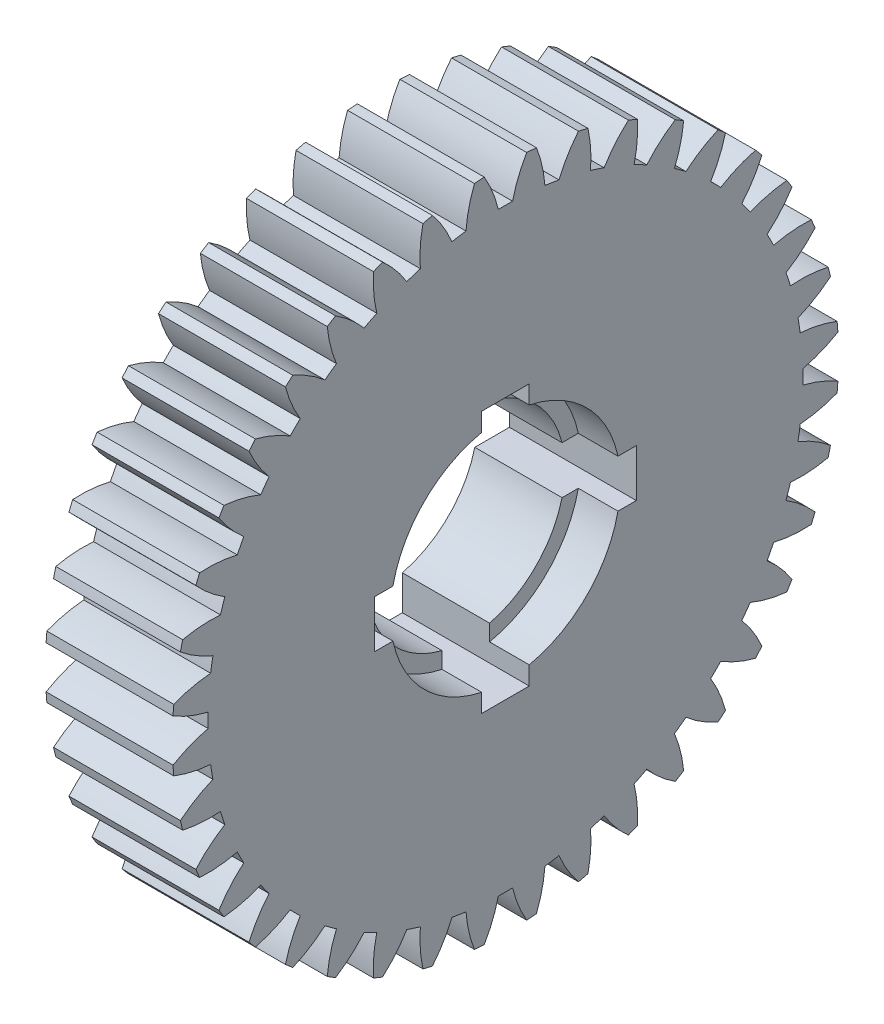
SolidWorks part; units mm, degrees
ref_plane "Plane1" through (0, 0, 0) normal (0, 0, 1) x (1, 0, 0)
ref_plane "Plane2" through (0, 0, 0) normal (0, 1, 0) x (1, 0, 0)
ref_plane "Plane3" through (0, 0, 0) normal (1, 0, 0) x (0, 0, -1)
sketch "HoldingSke" plane through (0, 0, 0) normal (0, 1, 0) x (1, 0, 0)
  line L0 (0, 0) -> (0.766, -0.6428)
  line L1 (-15, 0) -> (100, 0) construction
  line L2 (0, 0) -> (-2.1039, 2.3779)
  line L3 (0, 0) -> (-11.863, 4.5341)
  line L4 (0, 0) -> (6.6156, 5.5511)
  line L5 (0, 0) -> (-46.8476, -17.4728)
  line L6 (0, 0) -> (-6.6317, -4.4744)
  line L7 (-2.1039, 2.3779) -> (8.6586, 51.2059)
  line L8 (-76.2, 54.61) -> (-75.3, 54.61)
  line L9 (-71.009, 38.7566) -> (-53.1078, 45.2721)
  line L10 (-76.2, 71.12) -> (104.1128, 71.12)
  line L11 (0, 0) -> (-8, 0)
  line L12 (-76.2, 101.6) -> (-76.162, 101.6)
  line L13 (24.9733, 27.94) -> (52.9518, 28.4284)
  line L14 (24.9733, 27.94) -> (24.9743, 27.94)
  line L15 (24.9733, 27.94) -> (100.4006, 29.5858)
  line L16 (-63.627, -1) -> (-12.827, -1)
  circle A0 centre (0, 0) radius 2.5
  circle A1 centre (0, 0) radius 18.749
  circle A2 centre (0, 0) radius 37.5
  circle A3 centre (0, 0) radius 2.5
  dimension "MHD" = 37.498
  dimension "Hub_dia" = 75
  dimension "Bore" = 5
  dimension "MBD" = 5
  dimension "Num_teeth" = 40
  dimension "Pitch" = 1
  dimension "Overall_len" = 50
  dimension "Show_teeth" = 40
  dimension "Thickness" = 8
  dimension "OAL" = 50.0001
  dimension "T_dim" = 0.9
  dimension "Ap" = 20
  dimension "H" = 19.05
  dimension "Pitch_radius" = 180.3128
  dimension "Width" = 8
  dimension "Backlash" = 0.038
  dimension "Addendum_fac" = 1
  dimension "Dedendum_fac" = 1.25
  dimension "Clearance_fac" = 0.25
  dimension "Dedendum_add" = 0.001
  dimension "Module" = 1
sketch "BasProSke" plane through (0, 0, 0) normal (0, 1, 0) x (1, 0, 0)
  line L0 (-10, 0) -> (60, 0) construction
  line L1 (0, 0) -> (0, 21)
  line L2 (0, 0) -> (8, 0)
  line L3 (8, 0) -> (8, 21)
  line L4 (8, 21) -> (0, 21)
  dimension "Thickness" = 8
  dimension "Diameter" = 42
revolve "Base-Revolve" add sketch "BasProSke" angle 360 about L0
sketch "TooCutSke" plane through (0, 0, 0) normal (1, 0, 0) x (0, 0, -1)
  line L1 (0, 0) -> (0, 107) construction
  line L2 (0, 0) -> (-0.8517, 19.9819) construction
  line L3 (0, 0) -> (-3.1363, 39.8509) construction
  line L4 (-0.8517, 19.9819) -> (-1.5682, 19.9255) construction
  arc A0 (0.4487, 18.7436) -> (-0.4487, 18.7436) centre (0, 0) ccw
  arc A1 (1.3547, 20.9817) -> (-1.3547, 20.9817) centre (0, 0) ccw
  circle A2 centre (0, 0) radius 20 construction
  circle A3 centre (0, 0) radius 18.7939 construction
  arc A4 (-0.4487, 18.7436) -> (-1.3547, 20.9817) centre (-8.2322, 16.895) ccw
  arc A5 (1.3547, 20.9817) -> (0.4487, 18.7436) centre (8.2322, 16.895) ccw
  dimension "Root_dia" = 37.498
  dimension "Overcut_dia" = 42.0508
  dimension "Pitch_dia" = 40
  dimension "Base_dia" = 37.5877
  dimension "Flank_rad" = 8
  dimension "Half_ang" = 4.5
  dimension "Half_CT" = 0.7187
extrude "ToothCut" cut sketch "TooCutSke" along normal through all
fillet "Breaks" [suppressed] radius 0.02
fillet "RootFillets" [suppressed] radius 0.251
pattern_circular "TeethCuts" count 40 over 360 about axis through (0, 0, 0) along (1, 0, 0) of "ToothCut", "RootFillets", "Breaks"
sketch "HubNeaOneSke" plane through (0, 0, 0) normal (-1, 0, 0) x (0, 0, 1)
  circle A0 centre (0, 0) radius 18.749
  dimension "Diameter" = 37.498
extrude "HubNearOne" [suppressed] add sketch "HubNeaOneSke" along normal blind 42.0001
sketch "HubNeaBotSke" plane through (0, 0, 0) normal (-1, 0, 0) x (0, 0, 1)
  circle A0 centre (0, 0) radius 18.749
  dimension "Diameter" = 37.498
extrude "HubNearBoth" [suppressed] add sketch "HubNeaBotSke" along normal blind 21
ref_plane "FarPln" through (8, 0, 0) normal (1, 0, 0) x (0, 0, -1)
sketch "HubFarSke" plane through (8, 0, 0) normal (1, 0, 0) x (0, 0, -1)
  circle A0 centre (0, 0) radius 18.749
  dimension "Diameter" = 37.498
extrude "HubFar" [suppressed] add sketch "HubFarSke" along normal blind 21
sketch "BorSke" plane through (0, 0, 0) normal (1, 0, 0) x (0, 0, -1)
  circle A0 centre (0, 0) radius 2.5
  dimension "Diameter" = 5
extrude "Bore" cut sketch "BorSke" along normal mid plane 100.0001
sketch "KeySke" plane through (0, 0, 0) normal (1, 0, 0) x (0, 0, -1)
  line L0 (-1, 0) -> (-1, 3.4)
  line L1 (-1, 3.4) -> (1, 3.4)
  line L2 (1, 3.4) -> (1, 0)
  line L3 (0, 0) -> (0, 34) construction
  line L4 (-1, 0) -> (1, 0)
  dimension "Offset" = 3.4
  dimension "Width" = 2
extrude "Keyway" [suppressed] cut sketch "KeySke" along normal mid plane 100.0001
pattern_circular "Keyway2" [suppressed] count 2 every 90 about axis through (-10, 0, 0) along (1, 0, 0)
sketch "Sketch1" plane through (8, 0, 0) normal (1, 0, 0) x (0, 0, -1)
  circle A0 centre (-0.3641, 0) radius 30.3952
extrude "Cut-Extrude1" cut sketch "Sketch1" against normal blind 0.0001
sketch "Sketch2" plane through (7.9999, 0, 0) normal (1, 0, 0) x (0, 0, -1)
  line L1 (-1.5, 8.25) -> (1.5, 8.25)
  line L2 (-1.5, 8.25) -> (-1.5, 6.0673)
  line L3 (-1.5, -8.25) -> (1.5, -8.25)
  line L4 (1.5, 8.25) -> (1.5, 6.0673)
  line L5 (-6.0673, 1.5) -> (-8.25, 1.5)
  line L6 (-6.0673, -1.5) -> (-8.25, -1.5)
  line L7 (8.25, 1.5) -> (6.0673, 1.5)
  line L8 (8.25, 1.5) -> (8.25, -1.5)
  line L9 (8.25, -1.5) -> (6.0673, -1.5)
  line L10 (-8.25, 1.5) -> (-8.25, -1.5)
  line L11 (-1.5, -6.0673) -> (-1.5, -8.25)
  line L12 (1.5, -6.0673) -> (1.5, -8.25)
  arc A0 (-1.5, 6.0673) -> (-6.0673, 1.5) centre (0, 0) ccw
  arc A1 (-6.0673, -1.5) -> (-1.5, -6.0673) centre (0, 0) ccw
  arc A2 (1.5, -6.0673) -> (6.0673, -1.5) centre (0, 0) ccw
  arc A3 (6.0673, 1.5) -> (1.5, 6.0673) centre (0, 0) ccw
  dimension "D1" = 12.5
  dimension "D2" = 16.5
  dimension "D3" = 16.5
  dimension "D4" = 3
  dimension "D5" = 3
extrude "Cut-Extrude2" cut sketch "Sketch2" against normal through all
sketch "Sketch3" plane through (7.9999, 0, 0) normal (1, 0, 0) x (0, 0, -1)
  circle A0 centre (0, 0) radius 7.25
extrude "Cut-Extrude3" cut sketch "Sketch3" against normal blind 2.5
equation "' \"Module@HoldingSke\" = 6.35"
equation "' \"Num_teeth@HoldingSke\" = 12"
equation "' \"Ap@HoldingSke\" =  20"
equation "' \"Ap@HoldingSke\" = 20"
equation "' \"Width@HoldingSke\" = 0.5 * 25.4"
equation "' \"Hub_dia@HoldingSke\"= 1 * 25.4"
equation "' \"Hub_dia@HoldingSke\" = 1 * 25.4"
equation "' \"Overall_len@HoldingSke\" = 1.0 * 25.4"
equation "' \"Bore@HoldingSke\" = 0.75 * 25.4"
equation "' \"T_dim@HoldingSke\" = 0.1 * 25.4"
equation "' \"Width@KeySke\" = 0.25 * 25.4"
equation "' \"Show_teeth@HoldingSke\" = 13"
equation "' \"Backlash@HoldingSke\" = 0.009 * 25.4"
equation "' \"Addendum_fac@HoldingSke\" = 1.0"
equation "' \"Dedendum_fac@HoldingSke\" = 1.25"
equation "' \"Dedendum_add@HoldingSke\" = 0.00005 * 25.4"
equation "' \"Clearance_fac@HoldingSke\" = 0.25"
equation "\"Pitch@HoldingSke\" = 1 / \"Module@HoldingSke\""
equation "\"Overcut_dia@TooCutSke\" = (\"Num_teeth@HoldingSke\" + 2 * \"Addendum_fac@HoldingSke\") / \"Pitch@HoldingSke\" + 0.002 * 25.4"
equation "\"Pitch_dia@TooCutSke\" = \"Num_teeth@HoldingSke\" / \"Pitch@HoldingSke\""
equation "\"Base_dia@TooCutSke\" = \"Num_teeth@HoldingSke\" / \"Pitch@HoldingSke\" * cos((\"Ap@HoldingSke\"  * 3.14159265 / 180))"
equation "\"Root_dia@TooCutSke\" = (\"Num_teeth@HoldingSke\" + 2) / \"Pitch@HoldingSke\" - 2 * (\"Addendum_fac@HoldingSke\" + \"Dedendum_fac@HoldingSke\") / \"Pitch@HoldingSke\" - \"Dedendum_add@HoldingSke\" * 2"
equation "\"Half_ang@TooCutSke\" = 180 / \"Num_teeth@HoldingSke\""
equation "\"Half_CT@TooCutSke\" = \"Num_teeth@HoldingSke\" / \"Pitch@HoldingSke\" * sin((3.14159265 / 2 / \"Num_teeth@HoldingSke\")) / 2 - 7 * \"Backlash@HoldingSke\" / 4"
equation "\"Flank_rad@TooCutSke\" = \"Num_teeth@HoldingSke\" / \"Pitch@HoldingSke\" / 5"
equation "\"Radius@RootFillets\" = \"Clearance_fac@HoldingSke\" / \"Pitch@HoldingSke\" + \"Dedendum_add@HoldingSke\""
equation "\"Break_rad@Breaks\" = 0.02 / \"Pitch@HoldingSke\""
equation "\"Thickness@HoldingSke\" = \"Width@HoldingSke\""
equation "\"OAL@HoldingSke\" = \"Thickness@HoldingSke\""
equation "\"MHD@HoldingSke\" = (\"Num_teeth@HoldingSke\" + 2) / \"Pitch@HoldingSke\" - 2 * (\"Addendum_fac@HoldingSke\" + \"Dedendum_fac@HoldingSke\")  / \"Pitch@HoldingSke\" - \"Dedendum_add@HoldingSke\" * 2"
equation "\"MBD@HoldingSke\" = (\"Num_teeth@HoldingSke\" + 2) / \"Pitch@HoldingSke\" - 2 * (\"Addendum_fac@HoldingSke\" + \"Dedendum_fac@HoldingSke\")  / \"Pitch@HoldingSke\" - \"Dedendum_add@HoldingSke\" * 2 - 0.002 * 25.4"
equation "\"MHD@HoldingSke\" = ((sgn( \"MHD@HoldingSke\" - \"Hub_dia@HoldingSke\" )-1)*( \"MHD@HoldingSke\" - \"Hub_dia@HoldingSke\" ))/-2+ \"Hub_dia@HoldingSke\""
equation "\"MBD@HoldingSke\" = ((sgn( \"MBD@HoldingSke\" - \"Bore@HoldingSke\" )-1)*( \"MBD@HoldingSke\" - \"Bore@HoldingSke\" ))/-2+ \"Bore@HoldingSke\""
equation "\"OAL@HoldingSke\" = ((sgn( \"OAL@HoldingSke\" - \"Overall_len@HoldingSke\" )+1)*( \"OAL@HoldingSke\" - \"Overall_len@HoldingSke\" ))/2 + \"Overall_len@HoldingSke\" + 0.000002 * 25.4"
equation "\"Num_teeth@TeethCuts\" = int( \"Show_teeth@HoldingSke\" ) + 1"
equation "\"Num_teeth@TeethCuts\" = ((sgn( \"Num_teeth@TeethCuts\" - \"Num_teeth@HoldingSke\" )-1)*( \"Num_teeth@TeethCuts\" - \"Num_teeth@HoldingSke\" ))/-2+ \"Num_teeth@HoldingSke\""
equation "\"Num_teeth@TeethCuts\" = ((sgn( \"Num_teeth@TeethCuts\" - 2.0)+1)*( \"Num_teeth@TeethCuts\" - 2.0))/2 +2.0"
equation "\"Angle@TeethCuts\" = 360.0 / \"Num_teeth@HoldingSke\""
equation "\"Diameter@BasProSke\" = (\"Num_teeth@HoldingSke\" + 2 * \"Addendum_fac@HoldingSke\") / \"Pitch@HoldingSke\""
equation "\"Thickness@BasProSke\"  = \"Thickness@HoldingSke\""
equation "' \"Fillet_rad@BasProSke\" =  \"Thickness@HoldingSke\" * 0.05"
equation "' \"Fillet_rad@BasProSke\" = \"Thickness@HoldingSke\" * 0.05"
equation "\"MHD@HoldingSke\" = ((sgn( \"MHD@HoldingSke\" - \"Root_dia@TooCutSke\" )-1)*( \"MHD@HoldingSke\" - \"Root_dia@TooCutSke\" ))/-2+ \"Root_dia@TooCutSke\""
equation "\"Diameter@HubNeaOneSke\" = \"MHD@HoldingSke\""
equation "\"Length@HubNearOne\" = \"OAL@HoldingSke\" - \"Thickness@BasProSke\""
equation "\"Diameter@HubNeaBotSke\" = \"MHD@HoldingSke\""
equation "\"Length@HubNearBoth\" = ( \"OAL@HoldingSke\" - \"Thickness@BasProSke\" ) / 2.0"
equation "\"Thickness@FarPln\" = \"Thickness@BasProSke\""
equation "\"Diameter@HubFarSke\" = \"MHD@HoldingSke\""
equation "\"Length@HubFar\" = ( \"OAL@HoldingSke\" - \"Thickness@BasProSke\" ) / 2.0"
equation "\"Diameter@BorSke\" = \"MBD@HoldingSke\""
equation "\"D1@Bore\" = \"OAL@HoldingSke\" * 2.0"
equation "\"D1@Keyway\" = \"OAL@HoldingSke\" * 2.0"
equation "\"Offset@KeySke\" = \"T_dim@HoldingSke\" + \"MBD@HoldingSke\" / 2.0"
